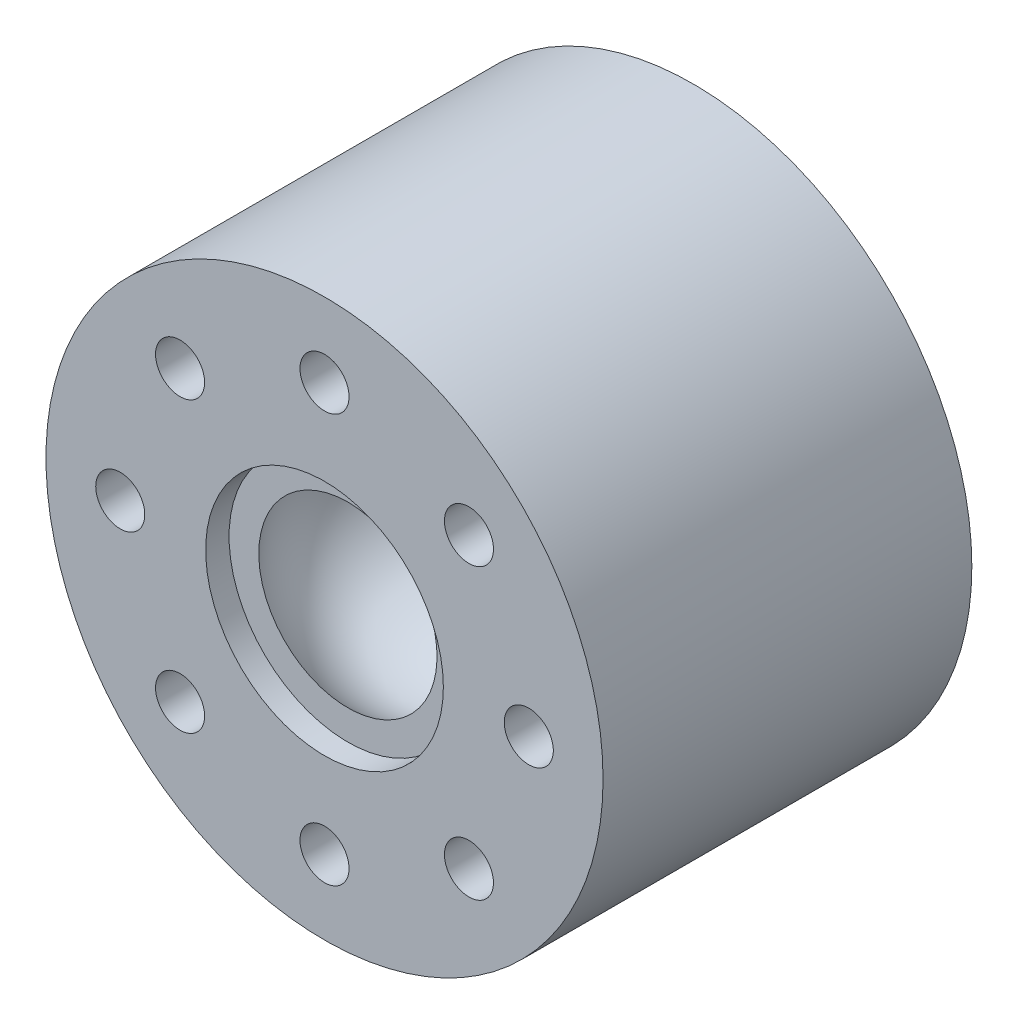
SolidWorks part; units mm, degrees
ref_plane "Front Plane" through (0, 0, 0) normal (0, 0, 1) x (1, 0, 0)
ref_plane "Top Plane" through (0, 0, 0) normal (0, 1, 0) x (1, 0, 0)
ref_plane "Right Plane" through (0, 0, 0) normal (1, 0, 0) x (0, 0, -1)
sketch "Sketch1" plane through (0, 0, 0) normal (0, 0, 1) x (1, 0, 0)
  circle A0 centre (0, 0) radius 37.5
  dimension "D1" = 75
extrude "Boss-Extrude1" add sketch "Sketch1" along normal blind 55 and the other way blind 10
sketch "Sketch2" plane through (0, 0, 55) normal (0, 0, 1) x (1, 0, 0)
  circle A0 centre (0, 0) radius 16
  dimension "D1" = 32
extrude "Cut-Extrude1" cut sketch "Sketch2" against normal blind 16
sketch "Sketch3" plane through (0, 0, 39) normal (0, 0, 1) x (1, 0, 0)
  circle A0 centre (0, 0) radius 16
  dimension "D1" = 32
extrude "Cut-Extrude2" cut sketch "Sketch3" against normal blind 2.5
sketch "Sketch4" plane through (0, 0, 0) normal (1, 0, 0) x (0, 0, -1)
  line L0 (-19.46, 12) -> (-19.46, 0)
  line L1 (-19.46, 0) -> (-36.5, 0)
  line L2 (-36.5, 0) -> (-36.5, 12)
  line L4 (-36.5, 16) -> (-36.5, -16) construction
  spline S0 degree 2 poles (-36.5, 12) (-27.947, 19.4408) (-19.46, 12) knots 0 0 0 1 1 1
  dimension "D4" = 15.72
  dimension "D1" = 12
  dimension "D2" = 12
  dimension "D3" = 17.04
revolve "Aortic Root" cut sketch "Sketch4" angle 360 about L1
sketch "Sketch6" plane through (0, 0, -10) normal (0, 0, -1) x (-1, 0, 0)
  circle A0 centre (0, 0) radius 8.9297
  dimension "D1" = 17.8594
extrude "Cut-Extrude3" cut sketch "Sketch6" against normal blind 23
sketch "Sketch7" plane through (0, 0, 55) normal (0, 0, 1) x (1, 0, 0)
  circle A1 centre (0, 0) radius 37.5
  dimension "D1" = 75
extrude "Cut-Extrude4" cut sketch "Sketch7" against normal blind 15.35
sketch "Sketch9" plane through (0, 0, -10) normal (0, 0, -1) x (-1, 0, 0)
  circle A0 centre (0, 0) radius 27.5
  circle A1 centre (0, -27.5) radius 3.302
  circle A2 centre (-19.4454, -19.4454) radius 3.302
  circle A3 centre (-27.5, 0) radius 3.302
  circle A4 centre (-19.4454, 19.4454) radius 3.302
  circle A5 centre (0, 27.5) radius 3.302
  circle A6 centre (19.4454, 19.4454) radius 3.302
  circle A7 centre (27.5, 0) radius 3.302
  circle A8 centre (19.4454, -19.4454) radius 3.302
  point P21 (0, 0)
  dimension "D1" = 55
  dimension "D2" = 6.604
  dimension "D3" = 8
extrude "Bolt holes" cut sketch "Sketch9" against normal through all contours A0 A7 | A0 A7 | A0 A8 | A0 A8 | A0 A1 | A0 A1 | A0 A2 | A0 A2 | A0 A3 | A0 A3 | A0 A4 | A0 A4 | A0 A5 | A0 A5 | A0 A6 | A0 A6
sketch "Sketch10" plane through (0, 0, -10) normal (0, 0, -1) x (-1, 0, 0)
  circle A0 centre (0, 0) radius 8.9297 construction
  circle A1 centre (-27.5, 0) radius 3.302 construction
  circle A2 centre (-19.4454, -19.4454) radius 3.302 construction
  circle A3 centre (0, -27.5) radius 3.302 construction
  circle A4 centre (19.4454, -19.4454) radius 3.302 construction
  circle A5 centre (27.5, 0) radius 3.302 construction
  circle A6 centre (19.4454, 19.4454) radius 3.302 construction
  circle A7 centre (0, 27.5) radius 3.302 construction
  circle A8 centre (-19.4454, 19.4454) radius 3.302 construction
  circle A9 centre (0, 0) radius 37.5 construction
  circle A10 centre (0, 0) radius 8.9297
  circle A11 centre (-27.5, 0) radius 3.302
  circle A12 centre (-19.4454, -19.4454) radius 3.302
  circle A13 centre (0, -27.5) radius 3.302
  circle A14 centre (19.4454, -19.4454) radius 3.302
  circle A15 centre (27.5, 0) radius 3.302
  circle A16 centre (19.4454, 19.4454) radius 3.302
  circle A17 centre (0, 27.5) radius 3.302
  circle A18 centre (-19.4454, 19.4454) radius 3.302
  circle A19 centre (0, 0) radius 37.5
sketch "Sketch12" plane through (0, 0, 0) normal (0, 1, 0) x (1, 0, 0)
  line L0 (0, -19.46) -> (0, -13)
  line L1 (0, -13) -> (8.9297, -13)
  line L2 (8.9297, -13) -> (12, -19.46)
  line L3 (12, -19.46) -> (0, -19.46)
  line L4 (8.9297, -13) -> (8.9297, 10) construction
revolve "Cut-Revolve1" cut sketch "Sketch12" angle 360 about L0
